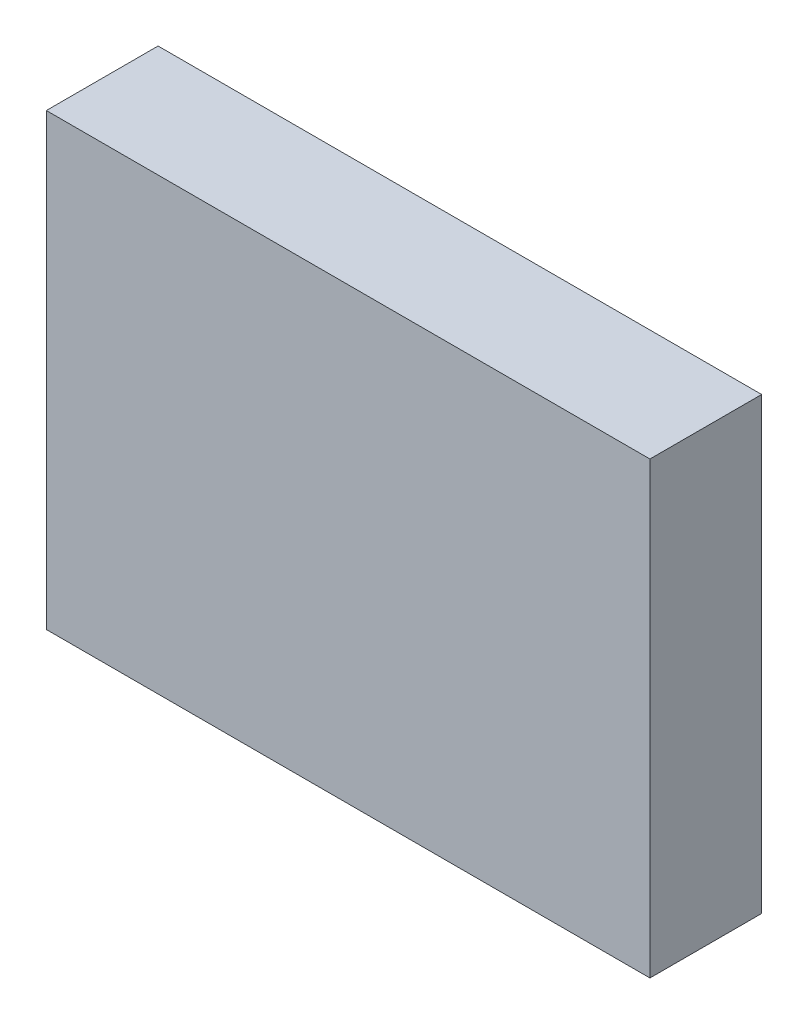
SolidWorks part; units mm, degrees
ref_plane "Plano frontal" through (0, 0, 0) normal (0, 0, 1) x (1, 0, 0)
ref_plane "Plano superior" through (0, 0, 0) normal (0, 1, 0) x (1, 0, 0)
ref_plane "Plano direito" through (0, 0, 0) normal (1, 0, 0) x (0, 0, -1)
sketch "Esboço1" plane through (0, 0, 0) normal (0, 0, 1) x (1, 0, 0)
  line L1 (-23.5, 17.5) -> (23.5, 17.5)
  line L2 (-23.5, 17.5) -> (-23.5, -17.5)
  line L3 (-23.5, -17.5) -> (23.5, -17.5)
  line L4 (23.5, 17.5) -> (23.5, -17.5)
  line L5 (-23.5, 17.5) -> (23.5, -17.5) construction
  line L6 (-23.5, -17.5) -> (23.5, 17.5) construction
  point P0 (0, 0)
  dimension "D1" = 47
  dimension "D2" = 35
extrude "Ressalto-extrusão1" add sketch "Esboço1" along normal blind 8.7
